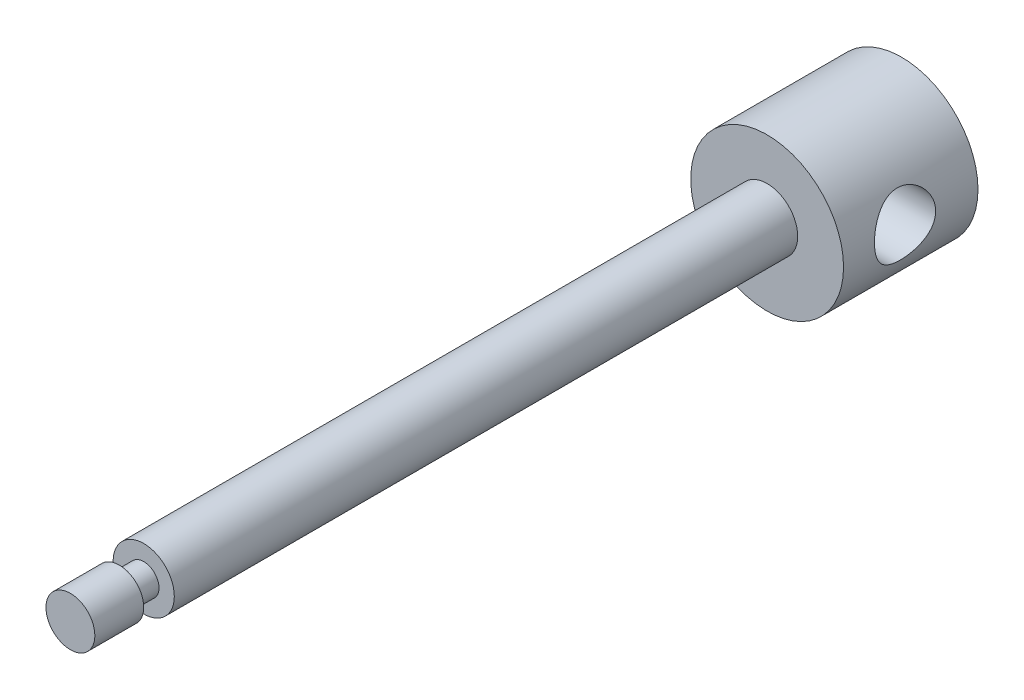
SolidWorks part; units mm, degrees
ref_plane "Front Plane" through (0, 0, 0) normal (0, 0, 1) x (1, 0, 0)
ref_plane "Top Plane" through (0, 0, 0) normal (0, 1, 0) x (1, 0, 0)
ref_plane "Right Plane" through (0, 0, 0) normal (1, 0, 0) x (0, 0, -1)
sketch "Sketch4" plane through (0, 0, 0) normal (0, 0, 1) x (1, 0, 0)
  circle A0 centre (0, 1.2144) radius 12.5
  dimension "D1" = 25
extrude "Boss-Extrude3" add sketch "Sketch4" along normal blind 22
ref_plane "Plane1" through (13, 0, 0) normal (1, 0, 0) x (0, 0, -1)
sketch "Sketch5" plane through (13, 0, 0) normal (1, 0, 0) x (0, 0, -1)
  line L0 (-22, 13.7144) -> (-22, -11.2856) construction
  circle A0 centre (-11.9193, 1.7552) radius 5
  dimension "D1" = 10
extrude "Cut-Extrude1" cut sketch "Sketch5" against normal blind 37
sketch "Sketch6" plane through (0, 0, 22) normal (0, 0, 1) x (1, 0, 0)
  circle A0 centre (0, 1.8053) radius 5
  dimension "D1" = 10
extrude "Boss-Extrude4" add sketch "Sketch6" along normal blind 102
sketch "Sketch7" plane through (0, 0, 124) normal (0, 0, 1) x (1, 0, 0)
  circle A0 centre (0, 1.7414) radius 2.5
  dimension "D1" = 5
extrude "Boss-Extrude5" add sketch "Sketch7" along normal blind 4
sketch "Sketch8" plane through (0, 0, 128) normal (0, 0, 1) x (1, 0, 0)
  circle A0 centre (0, 1.7414) radius 4
  dimension "D1" = 8
extrude "Boss-Extrude6" add sketch "Sketch8" along normal blind 8
